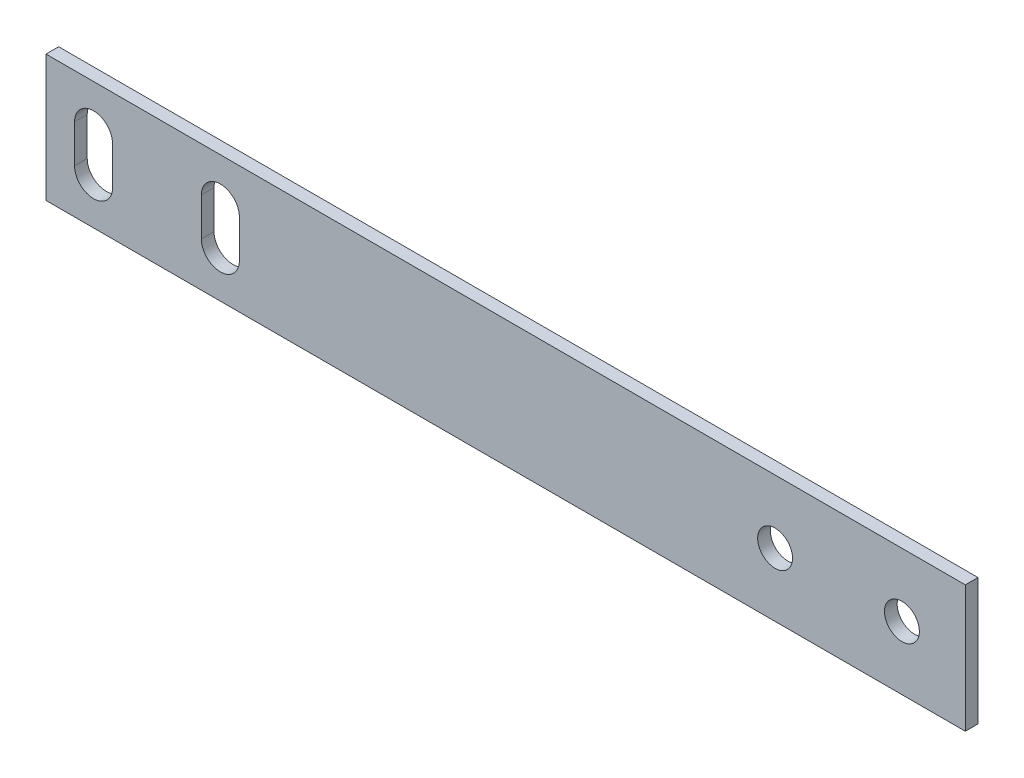
SolidWorks part; units mm, degrees
ref_plane "Front Plane" through (0, 0, 0) normal (0, 0, 1) x (1, 0, 0)
ref_plane "Top Plane" through (0, 0, 0) normal (0, 1, 0) x (1, 0, 0)
ref_plane "Right Plane" through (0, 0, 0) normal (1, 0, 0) x (0, 0, -1)
sketch "Sketch1" plane through (0, 0, 0) normal (0, 0, 1) x (1, 0, 0)
  line L0 (-65, -3) -> (-65, 3) construction
  line L1 (72.5, 10) -> (-72.5, 10)
  line L2 (72.5, 10) -> (72.5, -10)
  line L3 (72.5, -10) -> (-72.5, -10)
  line L4 (-72.5, 10) -> (-72.5, -10)
  line L5 (72.5, 10) -> (-72.5, -10) construction
  line L6 (72.5, -10) -> (-72.5, 10) construction
  line L7 (-68, -3) -> (-68, 3)
  line L8 (-62, -3) -> (-62, 3)
  line L9 (-45, -3) -> (-45, 3) construction
  line L10 (-48, -3) -> (-48, 3)
  line L11 (-42, -3) -> (-42, 3)
  circle A0 centre (62.5, 0) radius 2.75
  circle A1 centre (42.5, 0) radius 2.75
  arc A4 (-68, -3) -> (-62, -3) centre (-65, -3) ccw
  arc A5 (-62, 3) -> (-68, 3) centre (-65, 3) ccw
  arc A6 (-48, -3) -> (-42, -3) centre (-45, -3) ccw
  arc A7 (-42, 3) -> (-48, 3) centre (-45, 3) ccw
  point P0 (0, 0)
  point P12 (-65, 0)
  point P18 (-45, 0)
  point P24 (0, 0)
  point P25 (62.0976, -10.4021)
  point P26 (53.6657, 0)
  dimension "D1" = 5.5
  dimension "D2" = 20
  dimension "D9" = 3
  dimension "D3" = 145
  dimension "D4" = 20
  dimension "D5" = 10
  dimension "D6" = 7.5
  dimension "D7" = 20
  dimension "D8" = 6
extrude "Boss-Extrude1" add sketch "Sketch1" along normal blind 2
